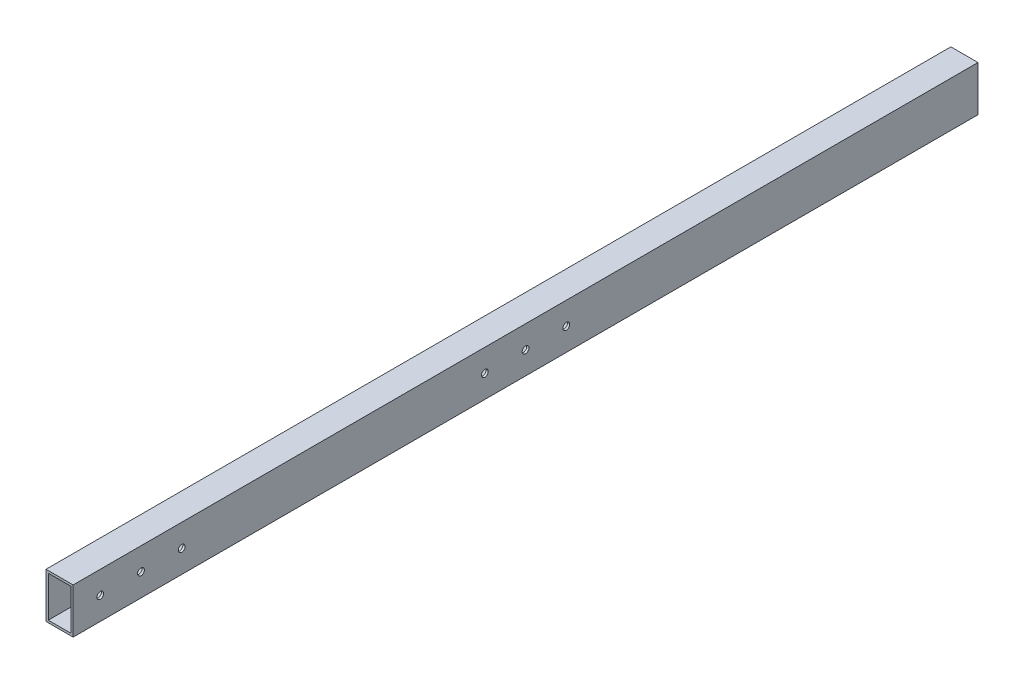
SolidWorks part; units mm, degrees
ref_plane "Front Plane" through (0, 0, 0) normal (0, 0, 1) x (1, 0, 0)
ref_plane "Top Plane" through (0, 0, 0) normal (0, 1, 0) x (1, 0, 0)
ref_plane "Right Plane" through (0, 0, 0) normal (1, 0, 0) x (0, 0, -1)
sketch "Sketch1" plane through (0, 0, 0) normal (0, 0, 1) x (1, 0, 0)
  line L1 (6, -10) -> (-6, -10)
  line L2 (6, -10) -> (6, 10)
  line L3 (6, 10) -> (-6, 10)
  line L4 (-6, -10) -> (-6, 10)
  line L5 (6, -10) -> (-6, 10) construction
  line L6 (6, 10) -> (-6, -10) construction
  line L7 (5, -9) -> (-5, -9)
  line L8 (5, -9) -> (5, 9)
  line L9 (5, 9) -> (-5, 9)
  line L10 (-5, -9) -> (-5, 9)
  line L11 (5, -9) -> (-5, 9) construction
  line L12 (5, 9) -> (-5, -9) construction
  point P0 (0, 0)
  point P6 (0, 0)
  dimension "D1" = 20
  dimension "D2" = 12
  dimension "D3" = 1
  dimension "D4" = 1
extrude "Boss-Extrude1" add sketch "Sketch1" along normal blind 400
sketch "Sketch2" plane through (6, 0, 0) normal (1, 0, 0) x (0, 0, -1)
  line L0 (-400, 0) -> (0, 0) construction
  line L1 (-400, -10) -> (-400, 10) construction
  line L2 (-400, -10) -> (0, -10) construction
  line L3 (-200, 0) -> (-200, 117.5205) construction
  line L4 (0, -10) -> (0, 10) construction
  line L5 (-400, 10) -> (-340, 10) construction
  line L6 (-400, 10) -> (-400, -10) construction
  line L7 (-400, -10) -> (-340, -10) construction
  line L8 (-340, 10) -> (-340, -10) construction
  circle A0 centre (-200, 0) radius 1.5
  circle A1 centre (-182, 0) radius 1.5
  circle A2 centre (-218, 0) radius 1.5
  circle A3 centre (-370, 0) radius 1.5
  circle A4 centre (-388, 0) radius 1.5
  circle A5 centre (-352, 0) radius 1.5
  dimension "D1" = 3
  dimension "D5" = 3
  dimension "D2" = 200
  dimension "D3" = 18
  dimension "D4" = 18
  dimension "D6" = 18
  dimension "D7" = 18
  dimension "D8" = 60
  dimension "D9" = 30
extrude "Cut-Extrude1" cut sketch "Sketch2" against normal blind 200
